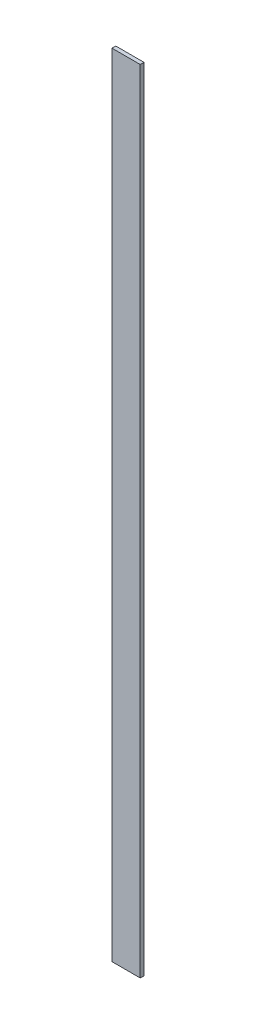
SolidWorks part; units mm, degrees
material "Zoltek Panex 33"
ref_plane "Plan de face" through (0, 0, 0) normal (0, 0, 1) x (1, 0, 0)
ref_plane "Plan de dessus" through (0, 0, 0) normal (0, 1, 0) x (1, 0, 0)
ref_plane "Plan de droite" through (0, 0, 0) normal (1, 0, 0) x (0, 0, -1)
sketch "Esquisse1" plane through (0, 0, 0) normal (0, 0, 1) x (1, 0, 0)
  line L1 (-1444.5512, 2477.1001) -> (-1414.5512, 2477.1001)
  line L2 (-1444.5512, 2477.1001) -> (-1444.5512, 1637.1001)
  line L3 (-1444.5512, 1637.1001) -> (-1414.5512, 1637.1001)
  line L4 (-1414.5512, 2477.1001) -> (-1414.5512, 1637.1001)
  dimension "D1" = 30
  dimension "D2" = 840
extrude "Boss.-Extru.1" add sketch "Esquisse1" along normal blind 4
